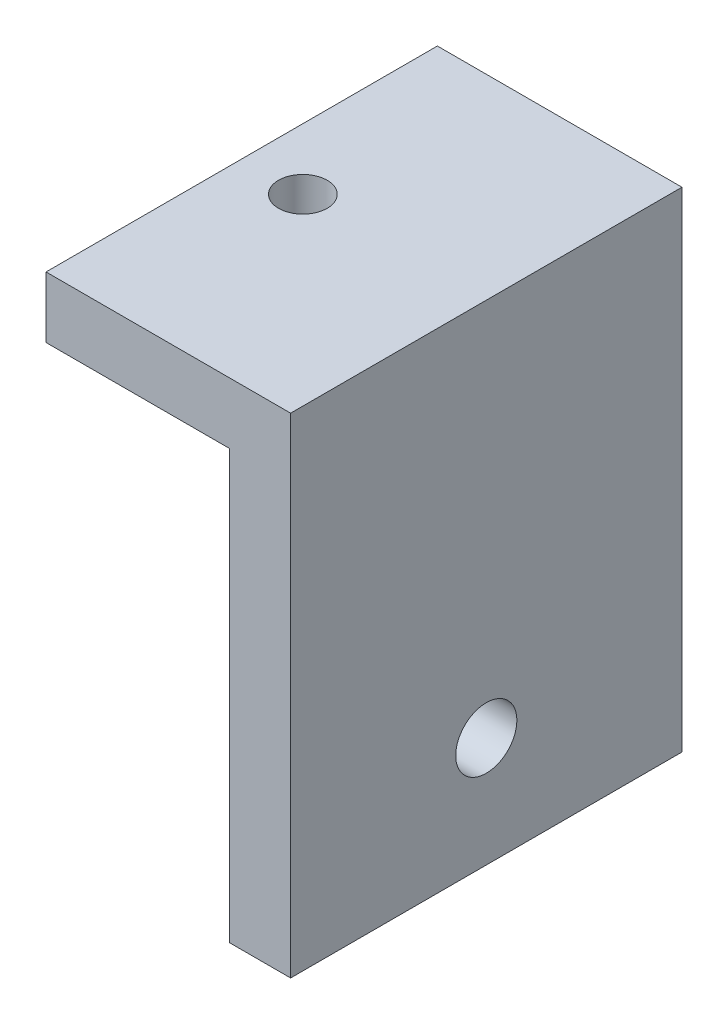
SolidWorks part; units mm, degrees
ref_plane "Front Plane" through (0, 0, 0) normal (0, 0, 1) x (1, 0, 0)
ref_plane "Top Plane" through (0, 0, 0) normal (0, 1, 0) x (1, 0, 0)
ref_plane "Right Plane" through (0, 0, 0) normal (1, 0, 0) x (0, 0, -1)
sketch "Sketch1" plane through (0, 0, 0) normal (0, 0, 1) x (1, 0, 0)
  line L1 (-17.3659, 21.5273) -> (8.0341, 21.5273)
  line L2 (-17.3659, 21.5273) -> (-17.3659, 15.1773)
  line L3 (-17.3659, 15.1773) -> (1.6841, 15.1773)
  line L4 (8.0341, 21.5273) -> (8.0341, 12.5659)
  line L6 (8.0341, 12.5659) -> (8.0341, -29.2727)
  line L7 (8.0341, -29.2727) -> (1.6841, -29.2727)
  line L8 (1.6841, 15.1773) -> (1.6841, -29.2727)
  dimension "D1" = 25.4
  dimension "D2" = 50.8
  dimension "D3" = 6.35
  dimension "D4" = 6.35
extrude "Boss-Extrude1" add sketch "Sketch1" along normal blind 40.64
hole_wizard "1/4 (0.25) Diameter Hole1" positions "Sketch2" profile "Sketch3" hole size "1/4" standard "ANSI Inch" end condition through all
sketch "Sketch2" plane through (8.0341, 0, 0) normal (1, 0, 0) x (0, 0, -1)
  line L0 (-40.64, -29.2727) -> (0, -29.2727) construction
  line L1 (-40.64, -29.2727) -> (-40.64, 21.5273) construction
  point P0 (-20.32, -17.8427)
  dimension "D1" = 11.43
  dimension "D2" = 20.32
sketch "Sketch3" plane through (8.0341, -17.8427, 20.32) normal (0, 1, 0) x (0, 0, -1)
  line L0 (0, 0) -> (0, 25.4)
  line L1 (0, 25.4) -> (3.175, 25.4)
  line L2 (3.175, 25.4) -> (3.175, 0)
  line L5 (3.175, 0) -> (0, 0)
  line L11 (0, -6.35) -> (0, 107.95) construction
  dimension "Thru Hole Dia." = 6.35
  dimension "Thru Hole Depth" = 25.4
hole_wizard "#8 (0.199) Diameter Hole2" positions "Sketch4" profile "Sketch5" hole size "#8" standard "ANSI Inch" end condition through all
sketch "Sketch4" plane through (0, 21.5273, 0) normal (0, 1, 0) x (1, 0, 0)
  line L0 (-17.3659, -40.64) -> (-17.3659, 0) construction
  line L1 (8.0341, 0) -> (-17.3659, 0) construction
  point P0 (-11.0159, -20.32)
  dimension "D1" = 6.35
  dimension "D2" = 20.32
sketch "Sketch5" plane through (-11.0159, 21.5273, 20.32) normal (1, 0, 0) x (0, 0, 1)
  line L0 (0, 0) -> (0, 50.8)
  line L1 (0, 50.8) -> (2.5273, 50.8)
  line L2 (2.5273, 50.8) -> (2.5273, 0)
  line L5 (2.5273, 0) -> (0, 0)
  line L11 (0, -6.35) -> (0, 107.95) construction
  dimension "Thru Hole Dia." = 5.0546
  dimension "Thru Hole Depth" = 50.8
